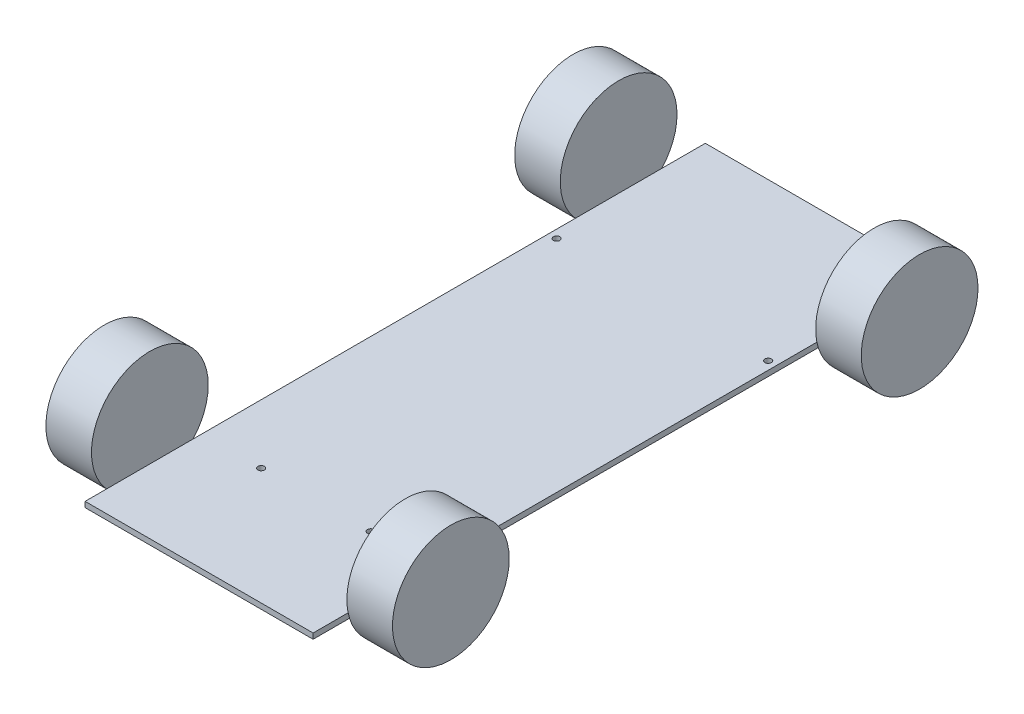
SolidWorks part; units mm, degrees
ref_plane "Front Plane" through (0, 0, 0) normal (0, 0, 1) x (1, 0, 0)
ref_plane "Top Plane" through (0, 0, 0) normal (0, 1, 0) x (1, 0, 0)
ref_plane "Right Plane" through (0, 0, 0) normal (1, 0, 0) x (0, 0, -1)
sketch "Sketch1" plane through (0, 0, 0) normal (0, 1, 0) x (1, 0, 0)
  line L0 (0, 0) -> (0, 192.9467) construction
  line L1 (-62.5, 170) -> (62.5, 170)
  line L2 (-62.5, 170) -> (-62.5, -170)
  line L3 (-62.5, -170) -> (62.5, -170)
  line L4 (62.5, 170) -> (62.5, -170)
  line L5 (-62.5, 170) -> (62.5, -170) construction
  line L6 (-62.5, -170) -> (62.5, 170) construction
  circle A0 centre (-58, 84) radius 1.778
  circle A1 centre (58, 84) radius 1.778
  circle A2 centre (-30, -106) radius 1.778
  circle A3 centre (30, -106) radius 1.778
  point P0 (0, 0)
  dimension "D5" = 3.556
  dimension "D1" = 340
  dimension "D2" = 125
  dimension "D3" = 60
  dimension "D4" = 116
  dimension "D6" = 190
  dimension "D7" = 86
extrude "Boss-Extrude1" add sketch "Sketch1" along normal blind 3
sketch "Sketch2" plane through (0, 0, 0) normal (1, 0, 0) x (0, 0, -1)
  line L0 (170, 3) -> (170, 0) construction
  line L2 (205.6585, -15) -> (-207.3895, -15) construction
  line L3 (170, 0) -> (-170, 0) construction
  circle A0 centre (130, 17) radius 32
  circle A1 centre (-127, 17) radius 32
  dimension "D1" = 64
  dimension "D2" = 257
  dimension "D3" = 40
  dimension "D4" = 15
extrude "Boss-Extrude2" add sketch "Sketch2" along normal blind 25 from offset 70 separate body
mirror "Mirror5" about plane through (0, 0, 0) normal (1, 0, 0) of bodies 102 103
